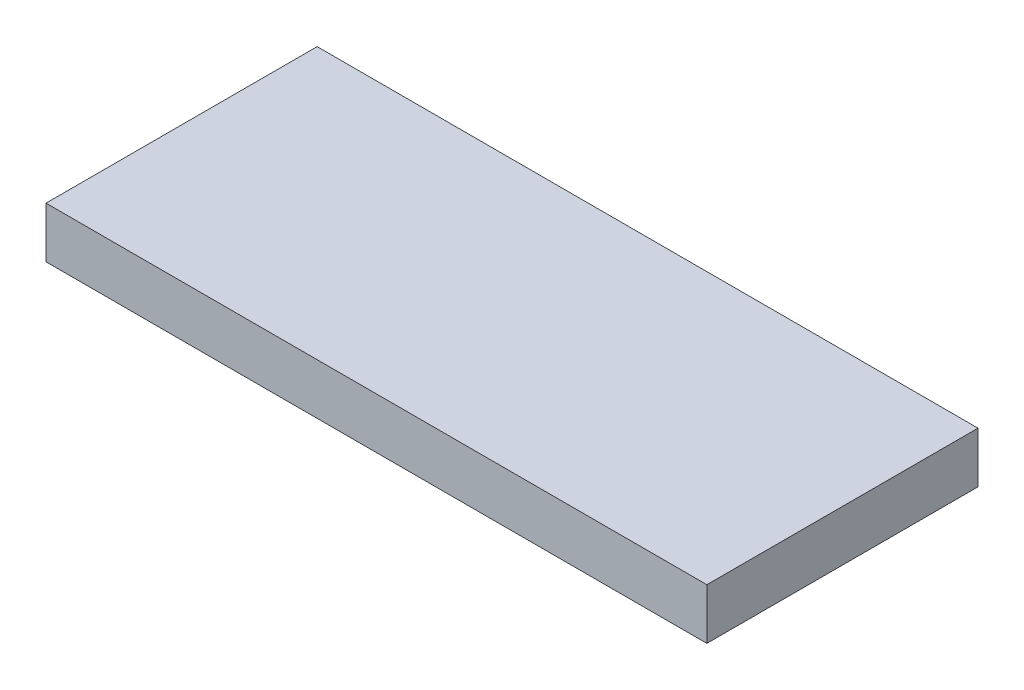
SolidWorks part; units mm, degrees
material "Polyurethane Foam Rigid"
ref_plane "Front Plane" through (0, 0, 0) normal (0, 0, 1) x (1, 0, 0)
ref_plane "Top Plane" through (0, 0, 0) normal (0, 1, 0) x (1, 0, 0)
ref_plane "Right Plane" through (0, 0, 0) normal (1, 0, 0) x (0, 0, -1)
sketch "Sketch1" plane through (0, 0, 0) normal (0, 1, 0) x (1, 0, 0)
  line L1 (-247.65, -101.6) -> (247.65, -101.6)
  line L2 (-247.65, -101.6) -> (-247.65, 101.6)
  line L3 (-247.65, 101.6) -> (247.65, 101.6)
  line L4 (247.65, -101.6) -> (247.65, 101.6)
  line L5 (-247.65, -101.6) -> (247.65, 101.6) construction
  line L6 (-247.65, 101.6) -> (247.65, -101.6) construction
  point P0 (0, 0)
extrude "Boss-Extrude1" add sketch "Sketch1" along normal blind 38.1
